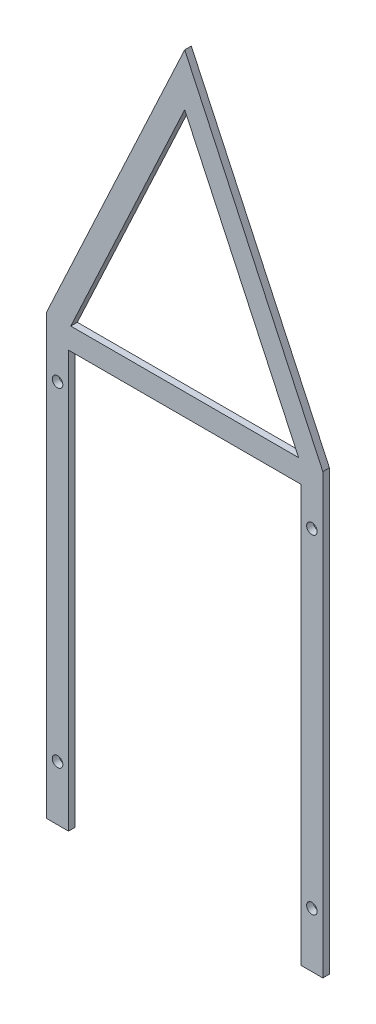
SolidWorks part; units mm, degrees
ref_plane "Front Plane" through (0, 0, 0) normal (0, 0, 1) x (1, 0, 0)
ref_plane "Top Plane" through (0, 0, 0) normal (0, 1, 0) x (1, 0, 0)
ref_plane "Right Plane" through (0, 0, 0) normal (1, 0, 0) x (0, 0, -1)
sketch "Sketch1" plane through (0, 0, 0) normal (0, 0, 1) x (1, 0, 0)
  line L1 (-63, -100) -> (-53, -100)
  line L2 (-63, -100) -> (-63, 100)
  line L3 (-63, 100) -> (63, 100)
  line L4 (63, -100) -> (63, 100)
  line L5 (-63, -100) -> (63, 100) construction
  line L6 (-63, 100) -> (63, -100) construction
  line L7 (53, -90) -> (53, 90)
  line L8 (-53, 90) -> (53, 90)
  line L9 (-53, -90) -> (-53, 90)
  line L10 (-53, -90) -> (-53, -100)
  line L11 (53, -90) -> (53, -100)
  line L12 (53, -100) -> (63, -100)
  line L13 (-63, -100) -> (63, -100) construction
  line L14 (-53, -90) -> (53, -90) construction
  point P0 (0, 0)
  dimension "D1" = 10
  dimension "FrameWidth" = 126
  dimension "FrameLength" = 200
extrude "Rectangle Rib" add sketch "Sketch1" along normal mid plane 3
sketch "Sketch2" plane through (0, 0, 1.5) normal (0, 0, 1) x (1, 0, 0)
  line L0 (-63, 100) -> (0, 235.1039)
  line L1 (0, 235.1039) -> (63, 100)
  line L2 (63, 100) -> (51.9662, 100)
  line L3 (63, 100) -> (-63, 100) construction
  line L4 (51.9662, 100) -> (0, 211.4419)
  line L5 (0, 211.4419) -> (-51.9662, 100)
  line L6 (-51.9662, 100) -> (-63, 100)
  line L7 (0, 235.1039) -> (0, 100) construction
  dimension "HalfAngle" = 25
  dimension "TopRibThickness" = 10
extrude "Triangle Rib" add sketch "Sketch2" against normal up to surface (3 mm away)
sketch "Sketch3" plane through (0, 0, 1.5) normal (0, 0, 1) x (1, 0, 0)
  line L0 (-63, 90) -> (-58, 90) construction
  line L1 (-63, 100) -> (-63, -100) construction
  line L2 (-58, 90) -> (-53, 90) construction
  line L3 (-58, 90) -> (-58, 75) construction
  dimension "ScrewEdgeOffset" = 5
  dimension "ScrewTopOffset" = 15
hole_wizard "M4 Clearance Hole1" positions "Sketch4" profile "Sketch5" hole size "M4" standard "ANSI Metric" end condition up to next
sketch "Sketch4" plane through (0, 0, 1.5) normal (0, 0, 1) x (1, 0, 0)
  point P0 (-58, 75)
sketch "Sketch5" plane through (-58, 75, 1.5) normal (1, 0, 0) x (0, -1, 0)
  line L0 (0, 0) -> (0, 3)
  line L1 (0, 3) -> (2.4, 3)
  line L2 (2.4, 3) -> (2.4, 0)
  line L5 (2.4, 0) -> (0, 0)
  line L11 (0, -6.35) -> (0, 107.95) construction
  dimension "Thru Hole Dia." = 4.8
  dimension "Thru Hole Depth" = 3
mirror "Mirror1" about plane through (0, 0, 0) normal (0, 1, 0) of "M4 Clearance Hole1" second plane through (0, 0, 0) second plane normal (1, 0, 0)
equation "\"FrameWidth\"= 3.30276"
